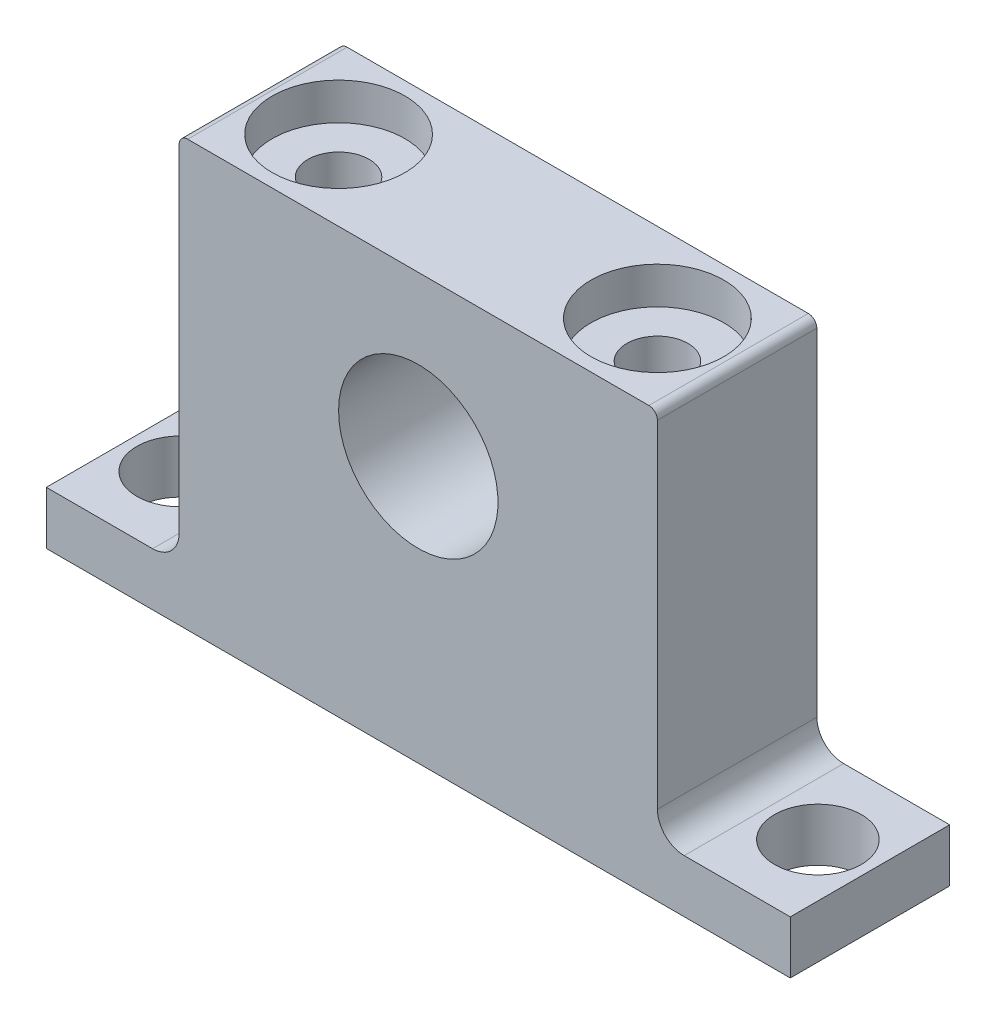
SolidWorks part; units mm, degrees
ref_plane "Front Plane" through (0, 0, 0) normal (0, 0, 1) x (1, 0, 0)
ref_plane "Top Plane" through (0, 0, 0) normal (0, 1, 0) x (1, 0, 0)
ref_plane "Right Plane" through (0, 0, 0) normal (1, 0, 0) x (0, 0, -1)
sketch "Sketch1" plane through (0, 0, 0) normal (0, 0, 1) x (1, 0, 0)
  line L1 (22.225, -12.7) -> (-22.225, -12.7)
  line L2 (22.225, -12.7) -> (22.225, -9.5357)
  line L3 (13.7795, 12.7) -> (-13.7795, 12.7)
  line L4 (-22.225, -12.7) -> (-22.225, -9.5357)
  line L7 (22.225, -9.5357) -> (15.8888, -9.5357)
  line L16 (-14.2875, -7.9482) -> (-14.2875, 3.175)
  line L17 (14.2875, -7.9344) -> (14.2875, 3.175)
  line L18 (-14.2875, 3.175) -> (-14.2875, 12.192)
  line L19 (14.2875, 3.175) -> (14.2875, 12.192)
  line L22 (-22.225, -9.5357) -> (-15.875, -9.5357)
  circle A0 centre (0, 3.175) radius 4.7625
  arc A1 (-15.875, -9.5357) -> (-14.2875, -7.9482) centre (-15.875, -7.9482) ccw
  arc A2 (15.8888, -9.5357) -> (14.2875, -7.9344) centre (15.8888, -7.9344) cw
  arc A3 (14.2875, 12.192) -> (13.7795, 12.7) centre (13.7795, 12.192) ccw
  arc A4 (-13.7795, 12.7) -> (-14.2875, 12.192) centre (-13.7795, 12.192) ccw
  point P0 (0, 0)
extrude "Boss-Extrude2" add sketch "Sketch1" along normal blind 9.525 contours A0 | L16 L18 A4 L3 A3 L19 L17 A2 L7 L2 L1 L4 L22 A1
hole_wizard "CBORE for #6 Binding Head Machine Screw1" positions "Sketch5" profile "Sketch6" counterbore size "#6" standard "ANSI Inch"
sketch "Sketch5" plane through (0, 12.7, 0) normal (0, 1, 0) x (1, 0, 0)
  line L2 (13.7795, 0) -> (-13.7795, 0) construction
  line L3 (-14.2875, -9.525) -> (-14.2875, 0) construction
  line L5 (14.2875, -9.525) -> (14.2875, 0) construction
  point P0 (9.525, -4.7625)
  point P2 (-9.525, -4.7625)
  dimension "D1" = 4.7625
  dimension "D2" = 4.7625
  dimension "D3" = 4.7625
sketch "Sketch6" plane through (9.525, 12.7, 4.7625) normal (1, 0, 0) x (0, 0, 1)
  line L0 (0, 0) -> (0, 15.3229)
  line L1 (0, 15.3229) -> (1.8288, 14.224)
  line L2 (1.8288, 14.224) -> (1.8288, 2.2098)
  line L3 (1.8288, 2.2098) -> (3.9688, 2.2098)
  line L4 (3.9688, 2.2098) -> (3.9688, 0)
  line L5 (3.9688, 0) -> (0, 0)
  line L10 (0, 15.3229) -> (-1.8288, 14.224) construction
  line L11 (0, -6.35) -> (0, 107.95) construction
  dimension "Hole Dia." = 3.6576
  dimension "Hole Depth" = 14.224
  dimension "C'Bore Dia." = 7.9375
  dimension "C'Bore Depth" = 2.2098
  dimension "Drill Angle" = 118
hole_wizard "#6 (0.204) Diameter Hole1" positions "Sketch8" profile "Sketch7" hole size "#6" standard "ANSI Inch" end condition through all
sketch "Sketch8" plane through (0, -9.5357, 0) normal (0, 1, 0) x (1, 0, 0)
  line L0 (-22.225, -9.525) -> (-22.225, 0) construction
  line L1 (22.225, -9.525) -> (22.225, 0) construction
  point P0 (-19.05, -4.699)
  point P2 (19.05, -4.699)
  dimension "D1" = 3.175
  dimension "D2" = 3.175
sketch "Sketch7" plane through (-19.05, -9.5357, 4.699) normal (1, 0, 0) x (0, 0, 1)
  line L0 (0, 0) -> (0, 3.1643)
  line L1 (0, 3.1643) -> (2.5908, 3.1643)
  line L2 (2.5908, 3.1643) -> (2.5908, 0)
  line L5 (2.5908, 0) -> (0, 0)
  line L11 (0, -6.35) -> (0, 107.95) construction
  dimension "Thru Hole Dia." = 5.1816
  dimension "Thru Hole Depth" = 3.1643
